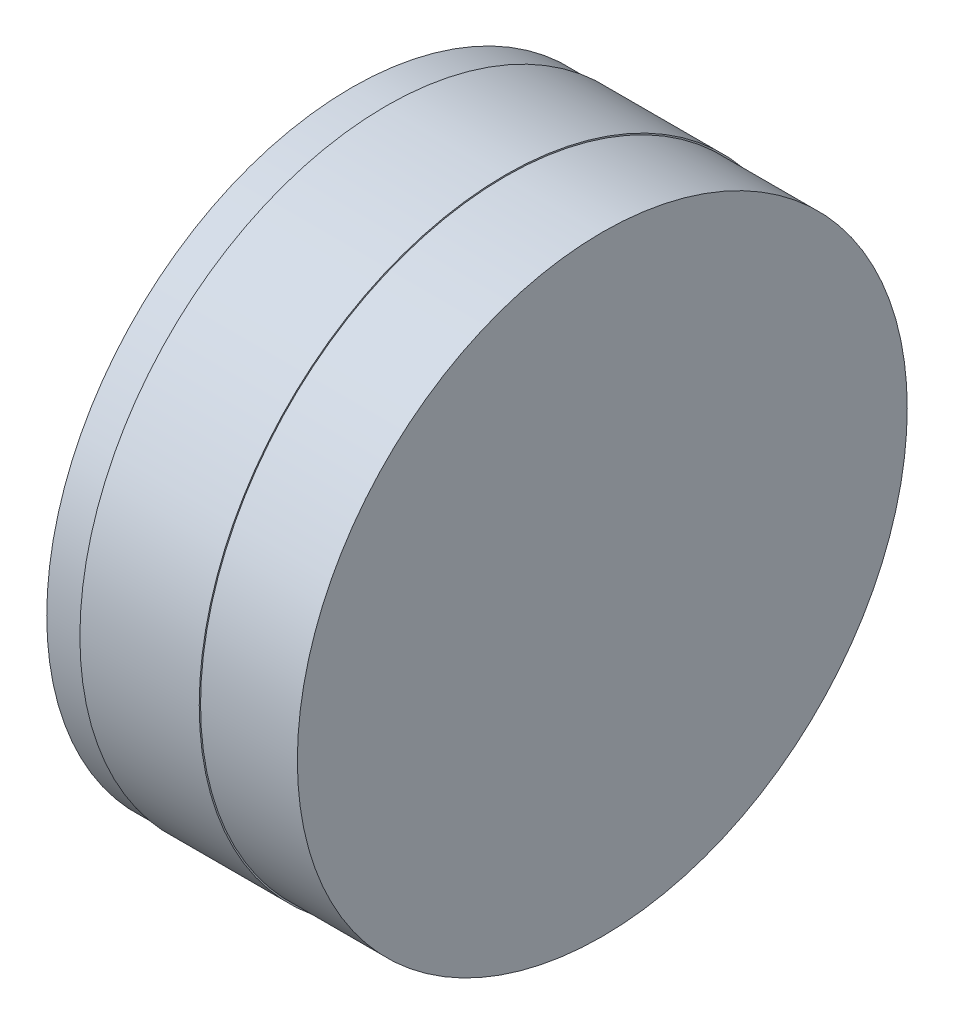
SolidWorks part; units mm, degrees
ref_plane "正面" through (0, 0, 0) normal (0, 0, 1) x (1, 0, 0)
ref_plane "平面" through (0, 0, 0) normal (0, 1, 0) x (1, 0, 0)
ref_plane "右側面" through (0, 0, 0) normal (1, 0, 0) x (0, 0, -1)
sketch "ｽｹｯﾁ1" plane through (0, 0, 0) normal (0, 0, 1) x (1, 0, 0)
  line L0 (0, 21) -> (0, 115)
  line L1 (0, 115) -> (13, 115)
  line L2 (13, 115) -> (13, 115.5)
  line L3 (13, 115.5) -> (58, 115.5)
  line L4 (58, 115.5) -> (58, 115)
  line L5 (58, 115) -> (94.5, 115)
  line L6 (94.5, 115) -> (94.5, 0)
  line L7 (94.5, 0) -> (13, 0)
  line L8 (13, 0) -> (13, 21)
  line L9 (13, 21) -> (0, 21)
  line L10 (0, 0) -> (94.5, 0) construction
revolve "回転1" add sketch "ｽｹｯﾁ1" angle 360 about L10
